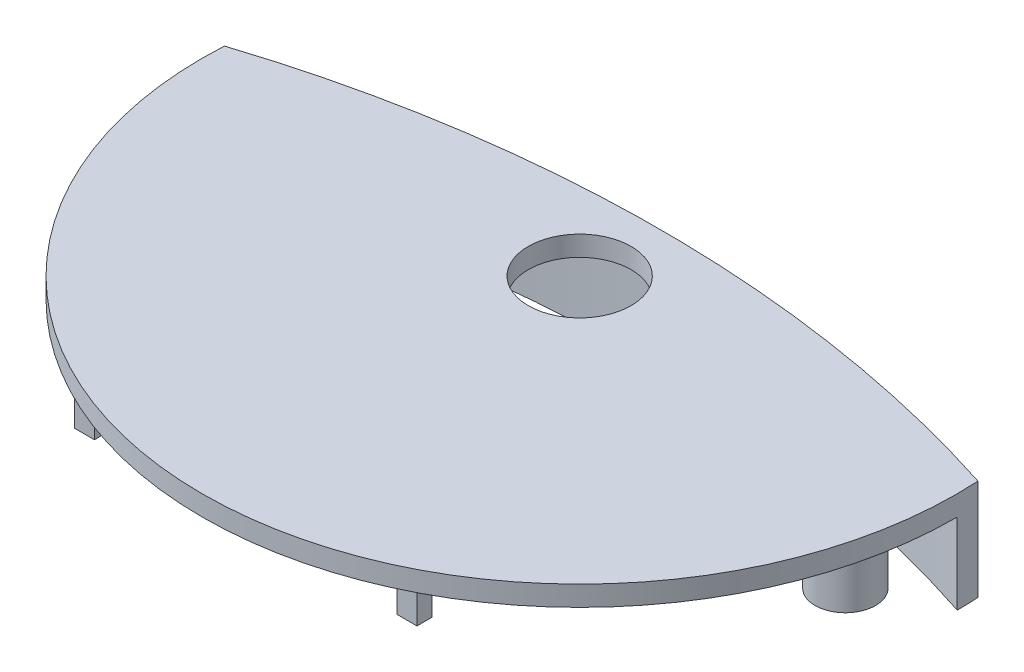
SolidWorks part; units mm, degrees
ref_plane "Front" through (0, 0, 0) normal (0, 0, 1) x (1, 0, 0)
ref_plane "Top" through (0, 0, 0) normal (0, 1, 0) x (1, 0, 0)
ref_plane "Right" through (0, 0, 0) normal (1, 0, 0) x (0, 0, -1)
sketch "草图1" plane through (0, 0, 0) normal (0, 1, 0) x (1, 0, 0)
  line L0 (-37.5, 0) -> (37.5, 0) construction
  line L1 (0, 0) -> (-36.9303, -6.5118) construction
  line L2 (0, 0) -> (36.9303, -6.5118) construction
  circle A0 centre (0, 0) radius 37.5 construction
  arc A3 (-37.3889, 2.139) -> (37.3889, 2.139) centre (0, 0) ccw
  arc A4 (-37.5, 0) -> (37.5, 0) centre (0, -114.1875) cw construction
  arc A5 (-37.3889, 2.139) -> (37.3889, 2.139) centre (0, -114.1875) cw
  arc A6 (-38.124, 1.9002) -> (38.124, 1.9002) centre (0, -114.1875) cw construction
  circle A7 centre (0, 0) radius 5.1
  point P5 (0, 0)
  point P8 (-32.0063, -5.6436)
  point P18 (0, 6)
  dimension "D1" = 75
  dimension "D8" = 6
  dimension "D10" = 74.9
  dimension "D11" = 10.2
  dimension "D2" = 10
  dimension "D3" = 10
  dimension "D4" = 5
  dimension "D9" = 2
extrude "凸台-拉伸1" add sketch "草图1" along normal blind 2
sketch "草图2" plane through (0, 0, 0) normal (0, -1, 0) x (1, 0, 0)
  arc A0 (37.3889, -2.139) -> (-37.3889, -2.139) centre (0, 0) ccw construction
  arc A1 (-37.5, 0) -> (37.5, 0) centre (0, 114.1875) ccw construction
  arc A2 (-37.3889, -2.139) -> (37.3889, -2.139) centre (0, 114.1875) ccw construction
  arc A3 (37.3889, -2.139) -> (37.45, -0.0164) centre (0, 0) ccw
  arc A4 (-37.45, -0.0164) -> (37.45, -0.0164) centre (0, 114.1875) ccw
  arc A5 (-37.3889, -2.139) -> (37.3889, -2.139) centre (0, 114.1875) ccw
  arc A6 (-37.45, -0.0164) -> (-37.3889, -2.139) centre (0, 0) ccw
extrude "凸台-拉伸2" add sketch "草图2" along normal blind 8
sketch "草图3" plane through (0, 0, 0) normal (0, -1, 0) x (1, 0, 0)
  line L0 (0, 0) -> (36.9303, 6.5118) construction
  line L1 (0, 0) -> (-36.9303, 6.5118) construction
  line L2 (-37.5, 0) -> (37.5, 0) construction
  line L3 (0, 0) -> (36.9303, 6.5118) construction
  line L4 (0, 0) -> (-36.9303, 6.5118) construction
  line L5 (-37.5, 0) -> (37.5, 0) construction
  circle A0 centre (0, 0) radius 37.5 construction
  circle A1 centre (0, 0) radius 37.5 construction
  circle A2 centre (-32.0063, 5.6436) radius 3
  circle A3 centre (-32.0063, 5.6436) radius 1.9
  circle A4 centre (32.0063, 5.6436) radius 3
  circle A5 centre (32.0063, 5.6436) radius 1.9
  point P7 (-32.0063, 5.6436)
  point P15 (32.0063, 5.6436)
  point P19 (0, 0)
  point P23 (0, 0)
  dimension "D2" = 6
  dimension "D3" = 3.8
  dimension "D1" = 5
extrude "凸台-拉伸3" add sketch "草图3" along normal blind 6
sketch "草图4" plane through (0, 0, 0) normal (0, -1, 0) x (1, 0, 0)
  line L0 (18, -1.6) -> (14, -1.6)
  line L1 (-14, -1.6) -> (-18, -1.6)
  line L2 (-14, -1.6) -> (-14, -5.6)
  line L3 (-14, -5.6) -> (-18, -5.6)
  line L4 (-18, -1.6) -> (-18, -5.6)
  line L5 (-14, -1.6) -> (-18, -5.6) construction
  line L6 (-14, -5.6) -> (-18, -1.6) construction
  line L7 (18, -1.6) -> (18, -5.6)
  line L8 (18, -5.6) -> (14, -5.6)
  line L9 (14, -1.6) -> (14, -5.6)
  line L10 (18, -1.6) -> (14, -5.6) construction
  line L11 (18, -5.6) -> (14, -1.6) construction
  line L12 (-16, -3.6) -> (16, -3.6) construction
  line L13 (17, 31.65) -> (15, 31.65)
  line L14 (-15, 31.65) -> (-17, 31.65)
  line L15 (-15, 31.65) -> (-15, 33.15)
  line L16 (-15, 33.15) -> (-17, 33.15)
  line L17 (-17, 31.65) -> (-17, 33.15)
  line L18 (-15, 31.65) -> (-17, 33.15) construction
  line L19 (-15, 33.15) -> (-17, 31.65) construction
  line L20 (17, 31.65) -> (17, 33.15)
  line L21 (17, 33.15) -> (15, 33.15)
  line L22 (15, 31.65) -> (15, 33.15)
  line L23 (17, 31.65) -> (15, 33.15) construction
  line L24 (17, 33.15) -> (15, 31.65) construction
  line L25 (-16, 32.4) -> (16, 32.4) construction
  point P0 (-16, -3.6)
  point P6 (-16, 32.4)
  point P7 (16, -3.6)
  point P21 (16, 32.4)
  dimension "D1" = 4
  dimension "D2" = 4
  dimension "D4" = 32
  dimension "D5" = 1.5
  dimension "D6" = 2
  dimension "D8" = 32
  dimension "D3" = 2
  dimension "D7" = 2
extrude "凸台-拉伸4" add sketch "草图4" along normal blind 2
sketch "草图5" plane through (0, -2, 0) normal (0, -1, 0) x (1, 0, 0)
  line L0 (-16, 32.4) -> (-16, -3.6) construction
  line L1 (-16, 32.4) -> (-16, -3.6) construction
  line L2 (16, 32.4) -> (-16, 32.4) construction
  line L3 (16, 32.4) -> (-16, 32.4) construction
  line L4 (16, -3.6) -> (16, 32.4) construction
  line L5 (16, -3.6) -> (16, 32.4) construction
  line L6 (-16, -3.6) -> (16, -3.6) construction
  line L7 (-16, -3.6) -> (16, -3.6) construction
  line L8 (-16.1, 32.5) -> (-16.1, 31.65)
  line L9 (-16.1, -3.7) -> (-14, -3.7)
  line L10 (16.1, -3.7) -> (16.1, -1.6)
  line L11 (16.1, 32.5) -> (15, 32.5)
  line L12 (-16.1, -1.6) -> (-16.1, -3.7)
  line L13 (-16.1, 31.65) -> (-17, 31.65)
  line L14 (-15, 32.5) -> (-15, 33.15)
  line L15 (-15, 33.15) -> (-17, 33.15)
  line L16 (-17, 31.65) -> (-17, 33.15)
  line L17 (-15, 31.65) -> (-17, 33.15) construction
  line L18 (-15, 33.15) -> (-17, 31.65) construction
  line L19 (-14, -5.1818) -> (-14, -1.6) construction
  line L21 (15, 33.15) -> (17, 33.15)
  line L22 (17, 31.65) -> (17, 33.15)
  line L23 (15, 31.65) -> (17, 33.15) construction
  line L24 (15, 33.15) -> (17, 31.65) construction
  line L25 (14, -5.6) -> (18, -5.6)
  line L26 (14, -5.6) -> (14, -3.7)
  line L27 (16.1, -1.6) -> (18, -1.6)
  line L28 (18, -5.6) -> (18, -1.6)
  line L29 (14, -5.6) -> (18, -1.6) construction
  line L30 (14, -1.6) -> (18, -5.6) construction
  line L31 (-14, -6.0211) -> (-18, -6.0211)
  line L32 (-14, -6.0211) -> (-14, -3.7)
  line L33 (-16.1, -1.6) -> (-18, -1.6)
  line L34 (-18, -6.0211) -> (-18, -1.6)
  line L35 (-14, -6.0211) -> (-18, -1.6) construction
  line L36 (-14.4123, -1.6383) -> (-18, -6.0211) construction
  line L37 (-16.1, 32.5) -> (-16.1, -3.7) construction
  line L38 (14, -3.7) -> (16.1, -3.7)
  line L39 (-16.1, -3.7) -> (16.1, -3.7) construction
  line L40 (16.1, 31.65) -> (17, 31.65)
  line L41 (15, 32.5) -> (15, 33.15)
  line L42 (-15, 32.5) -> (-16.1, 32.5)
  line L43 (16.1, 32.5) -> (-16.1, 32.5) construction
  line L44 (16.1, 31.65) -> (16.1, 32.5)
  line L45 (16.1, -3.7) -> (16.1, 32.5) construction
  dimension "D1" = 0.1
extrude "凸台-拉伸5" add sketch "草图5" along normal blind 1
